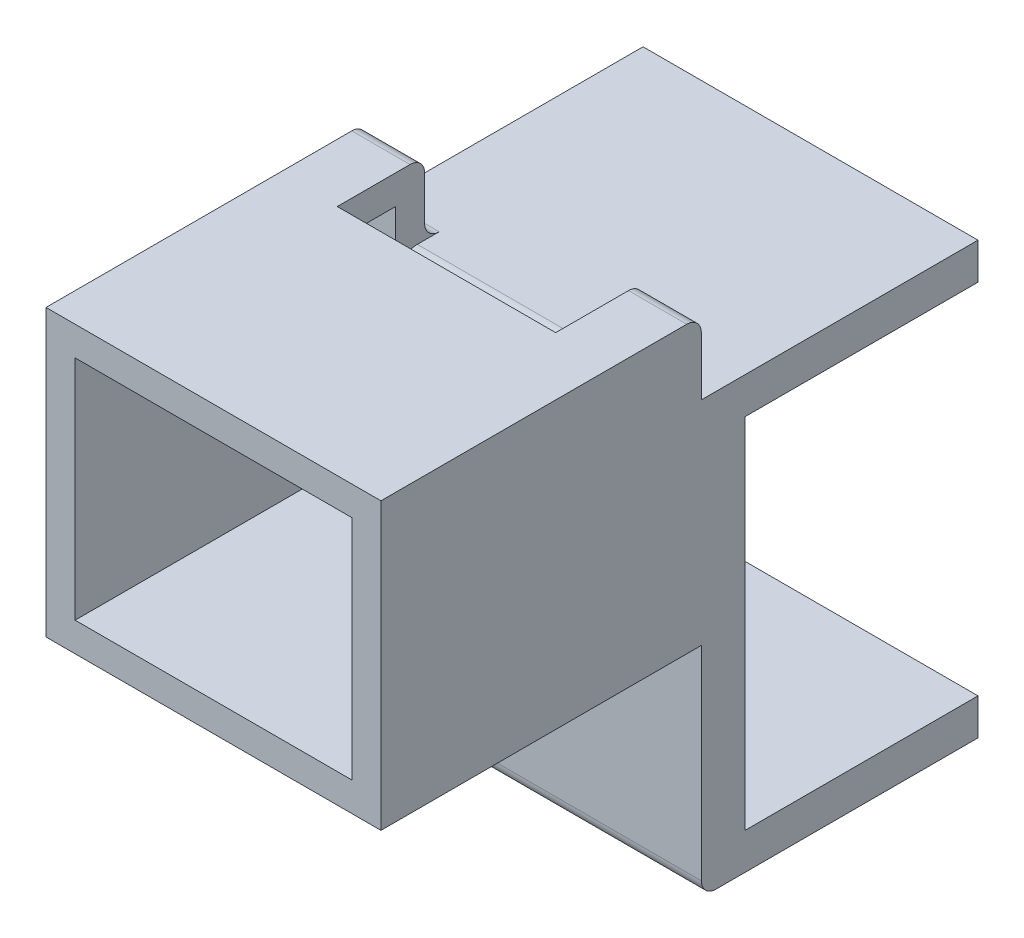
SolidWorks part; units mm, degrees
ref_plane "Plan de face" through (0, 0, 0) normal (0, 0, 1) x (1, 0, 0)
ref_plane "Plan de dessus" through (0, 0, 0) normal (0, 1, 0) x (1, 0, 0)
ref_plane "Plan de droite" through (0, 0, 0) normal (1, 0, 0) x (0, 0, -1)
sketch "Esquisse1" plane through (0, 0, 0) normal (0, 0, 1) x (1, 0, 0)
  line L1 (0, 0) -> (11.5, 0)
  line L2 (0, 0) -> (0, 9.8)
  line L3 (0, 9.8) -> (11.5, 9.8)
  line L4 (11.5, 0) -> (11.5, 9.8)
  dimension "D1" = 11.5
  dimension "D2" = 9.8
extrude "Boss.-Extru.1" add sketch "Esquisse1" along normal blind 11
sketch "Esquisse2" plane through (0, 0, 11) normal (0, 0, 1) x (1, 0, 0)
  line L0 (0, 9.8) -> (0, 0) construction
  line L1 (1, 1) -> (10.5, 1)
  line L2 (1, 1) -> (1, 8.8)
  line L3 (1, 8.8) -> (10.5, 8.8)
  line L4 (10.5, 1) -> (10.5, 8.8)
  line L5 (0, 0) -> (11.5, 0) construction
  line L6 (11.5, 0) -> (11.5, 9.8) construction
  line L7 (11.5, 9.8) -> (0, 9.8) construction
  dimension "D1" = 1
  dimension "D2" = 1
  dimension "D3" = 1
  dimension "D4" = 1
extrude "Enlèv. mat.-Extru.1" cut sketch "Esquisse2" against normal blind 10
sketch "Esquisse3" plane through (0, 9.8, 0) normal (0, 1, 0) x (1, 0, 0)
  line L0 (11.5, 0) -> (0, 0) construction
  line L1 (2, 0) -> (9.5, 0)
  line L2 (2, 0) -> (2, -3)
  line L3 (2, -3) -> (9.5, -3)
  line L4 (9.5, 0) -> (9.5, -3)
  line L5 (0, -11) -> (0, 0) construction
  line L6 (11.5, -11) -> (11.5, 0) construction
  dimension "D1" = 0
  dimension "D2" = 2
  dimension "D3" = 2
  dimension "D4" = 3
extrude "Enlèv. mat.-Extru.2" cut sketch "Esquisse3" against normal blind 2.5
fillet "Congé1" radius 0.75 2 edges at (5.75, 7.3, 1) (5.75, 8.8, 3)
sketch "Esquisse4" plane through (0, 0, 0) normal (0, 0, -1) x (-1, 0, 0)
  line L0 (-11.5, 0) -> (-11.5, 9.8) construction
  line L1 (-11.5, -7.5) -> (0, -7.5)
  line L2 (-11.5, -7.5) -> (-11.5, 7.3)
  line L3 (-11.5, 7.3) -> (0, 7.3)
  line L4 (0, -7.5) -> (0, 7.3)
  line L5 (0, 9.8) -> (0, 0) construction
  line L6 (0, 0) -> (-11.5, 0) construction
  line L7 (-11.5, 9.8) -> (-9.5, 9.8) construction
  point P12 (0, 0)
  dimension "D1" = 0
  dimension "D2" = 0
  dimension "D3" = 7.5
  dimension "D4" = 2.5
  dimension "D5" = 14.8
extrude "Boss.-Extru.2" add sketch "Esquisse4" along normal blind 1.5
sketch "Esquisse5" plane through (0, 0, -1.5) normal (0, 0, -1) x (-1, 0, 0)
  line L0 (-11.5, 7.3) -> (-11.5, -7.5) construction
  line L1 (-11.5, 6.05) -> (0, 6.05)
  line L2 (-11.5, 6.05) -> (-11.5, 7.3)
  line L3 (-11.5, 7.3) -> (0, 7.3)
  line L4 (0, 6.05) -> (0, 7.3)
  line L5 (0, -7.5) -> (0, 7.3) construction
  line L6 (0, 7.3) -> (-11.5, 7.3) construction
  line L7 (-11.5, -7.5) -> (0, -7.5)
  line L8 (-11.5, -7.5) -> (-11.5, -6.25)
  line L9 (-11.5, -6.25) -> (0, -6.25)
  line L10 (0, -7.5) -> (0, -6.25)
  line L11 (-11.5, -7.5) -> (0, -7.5) construction
  dimension "D1" = 0
  dimension "D2" = 0
  dimension "D3" = 0
  dimension "D4" = 1.25
  dimension "D5" = 0
  dimension "D6" = 0
  dimension "D7" = 1.25
extrude "Boss.-Extru.3" add sketch "Esquisse5" along normal blind 8
fillet "Congé2" radius 0.5 1 edges at (5.75, -7.5, 0)
fillet "Congé3" radius 0.5 3 edges at (1, 9.8, 0) (10.5, 9.8, 0) (1, 7.3, 0)
